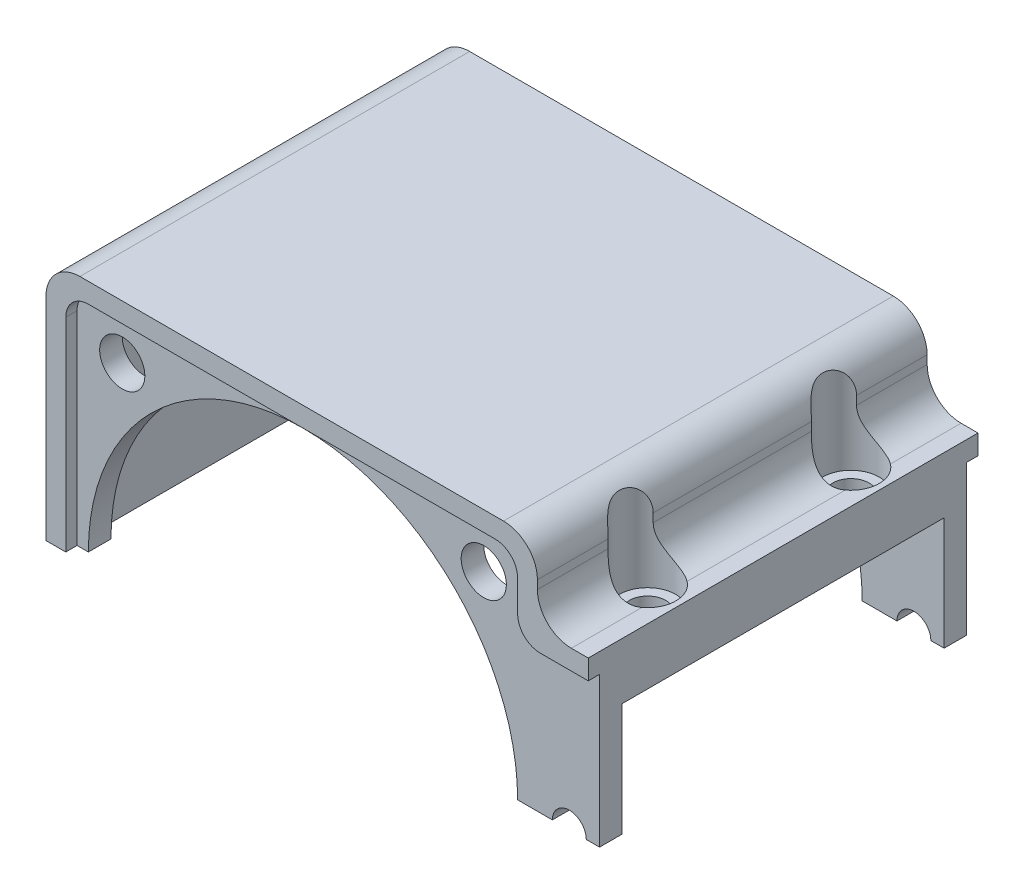
SolidWorks part; units mm, degrees
ref_plane "前视基准面" through (0, 0, 0) normal (0, 0, 1) x (1, 0, 0)
ref_plane "上视基准面" through (0, 0, 0) normal (0, 1, 0) x (1, 0, 0)
ref_plane "右视基准面" through (0, 0, 0) normal (1, 0, 0) x (0, 0, -1)
sketch "草图1" plane through (0, 0, 0) normal (0, 0, 1) x (1, 0, 0)
  line L5 (-20.25, 0) -> (-20.25, 17.25)
  line L6 (-17.25, 20.25) -> (17.25, 20.25)
  line L11 (23.25, 10) -> (26.25, 10)
  line L12 (20.25, 17.25) -> (20.25, 13)
  line L13 (-20.25, 0) -> (-21.75, 0)
  line L15 (0, 21.75) -> (-18.75, 21.75)
  line L16 (-21.75, 18.75) -> (-21.75, 0)
  line L17 (26.25, 10) -> (26.25, 15)
  line L21 (26.25, 15) -> (24.75, 15)
  line L22 (18.75, 21.75) -> (0, 21.75)
  line L23 (21.75, 18) -> (21.75, 18.75)
  arc A0 (24.75, 15) -> (21.75, 18) centre (24.75, 18) cw
  arc A1 (20.25, 13) -> (23.25, 10) centre (23.25, 13) ccw
  arc A2 (21.75, 18.75) -> (18.75, 21.75) centre (18.75, 18.75) ccw
  arc A3 (17.25, 20.25) -> (20.25, 17.25) centre (17.25, 17.25) cw
  arc A4 (-20.25, 17.25) -> (-17.25, 20.25) centre (-17.25, 17.25) cw
  arc A5 (-18.75, 21.75) -> (-21.75, 18.75) centre (-18.75, 18.75) ccw
  dimension "D1" = 3
extrude "凸台-拉伸1" add sketch "草图1" along normal blind 28.5
sketch "草图2" plane through (0, 0, 28.5) normal (0, 0, 1) x (1, 0, 0)
  line L0 (-21.75, 0) -> (26.25, 0)
  line L1 (26.25, 0) -> (26.25, 15)
  line L2 (26.25, 15) -> (24.75, 15)
  line L3 (21.75, 18) -> (21.75, 18.75)
  line L4 (18.75, 21.75) -> (-18.75, 21.75)
  line L5 (-21.75, 18.75) -> (-21.75, 0)
  arc A0 (24.75, 15) -> (21.75, 18) centre (24.75, 18) cw
  arc A1 (21.75, 18.75) -> (18.75, 21.75) centre (18.75, 18.75) ccw
  arc A2 (-18.75, 21.75) -> (-21.75, 18.75) centre (-18.75, 18.75) ccw
  dimension "D1" = 3
extrude "凸台-拉伸2" add sketch "草图2" along normal blind 3
sketch "草图3" plane through (0, 0, 0) normal (0, 0, -1) x (-1, 0, 0)
  line L0 (21.75, 0) -> (-26.25, 0)
  line L1 (-26.25, 0) -> (-26.25, 15)
  line L2 (-26.25, 15) -> (-24.75, 15)
  line L3 (-21.75, 18) -> (-21.75, 18.75)
  line L4 (-18.75, 21.75) -> (18.75, 21.75)
  line L5 (21.75, 18.75) -> (21.75, 0)
  arc A0 (-24.75, 15) -> (-21.75, 18) centre (-24.75, 18) ccw
  arc A1 (-21.75, 18.75) -> (-18.75, 21.75) centre (-18.75, 18.75) cw
  arc A2 (18.75, 21.75) -> (21.75, 18.75) centre (18.75, 18.75) cw
  dimension "D1" = 3
extrude "凸台-拉伸3" add sketch "草图3" along normal blind 3
sketch "草图4" plane through (0, 0, 31.5) normal (0, 0, 1) x (1, 0, 0)
  line L0 (26.25, 13.25) -> (26.25, 0)
  line L1 (-21.75, 0) -> (26.25, 0) construction
  line L2 (-20, 0) -> (-20, 18)
  line L3 (-18, 20) -> (18, 20)
  line L4 (26.25, 0) -> (-20, 0)
  line L5 (26.25, 0) -> (26.25, 15) construction
  line L6 (26.25, 13.25) -> (22, 13.25)
  line L7 (20, 15.25) -> (20, 18)
  arc A0 (18, 20) -> (20, 18) centre (18, 18) cw
  arc A1 (22, 13.25) -> (20, 15.25) centre (22, 15.25) cw
  arc A2 (-20, 18) -> (-18, 20) centre (-18, 18) cw
  dimension "D1" = 2
extrude "切除-拉伸1" cut sketch "草图4" against normal blind 1
sketch "草图5" plane through (0, 0, -3) normal (0, 0, -1) x (-1, 0, 0)
  line L0 (0, 0) -> (20, 0)
  line L1 (-26.25, 0) -> (21.75, 0) construction
  line L2 (20, 0) -> (20, 18)
  line L3 (18, 20) -> (-18, 20)
  line L4 (0, 0) -> (-26.25, 0)
  line L5 (-26.25, 15) -> (-26.25, 0) construction
  line L6 (-26.25, 13.25) -> (-22, 13.25)
  line L7 (-20, 15.25) -> (-20, 18)
  line L8 (-26.25, 0) -> (-26.25, 13.25)
  arc A0 (-22, 13.25) -> (-20, 15.25) centre (-22, 15.25) ccw
  arc A1 (-18, 20) -> (-20, 18) centre (-18, 18) ccw
  arc A2 (20, 18) -> (18, 20) centre (18, 18) ccw
  dimension "D1" = 2
extrude "切除-拉伸2" cut sketch "草图5" against normal blind 1
sketch "草图6" plane through (0, 0, 30.5) normal (0, 0, 1) x (1, 0, 0)
  line L0 (22.074, 0) -> (25.074, 0)
  line L36 (-11.5439, 13.6652) -> (-5.0528, 7.1742)
  line L39 (-1.5, 17.8255) -> (-1.5, 8.6458)
  line L40 (1.5, 17.8255) -> (1.5, 8.6458)
  line L43 (11.5439, 13.6652) -> (5.0528, 7.1742)
  line L44 (13.6652, 11.5439) -> (7.1742, 5.0528)
  line L47 (17.8255, 1.5) -> (8.6458, 1.5)
  line L52 (-4, 0) -> (4, 0)
  line L53 (-17.8255, 1.5) -> (-8.6458, 1.5)
  line L58 (-13.6652, 11.5439) -> (-7.1742, 5.0528)
  circle A0 centre (-16, 16) radius 2
  circle A1 centre (16, 16) radius 2
  arc A3 (22.074, 0) -> (25.074, 0) centre (23.574, 0) cw
  arc A7 (-4, 0) -> (4, 0) centre (0, 0) cw
  arc A9 (18.8159, 2.6389) -> (17.8255, 1.5) centre (17.8255, 2.5) cw
  arc A35 (-18.8159, 2.6389) -> (-15.1708, 11.4388) centre (0, 0) cw
  arc A36 (-7.6852, 2.2222) -> (-7.0056, 3.8629) centre (0, 0) cw
  arc A37 (-3.8629, 7.0056) -> (-2.2222, 7.6852) centre (0, 0) cw
  arc A38 (2.2222, 7.6852) -> (3.8629, 7.0056) centre (0, 0) cw
  arc A39 (7.0056, 3.8629) -> (7.6852, 2.2222) centre (0, 0) cw
  arc A40 (-11.4388, 15.1708) -> (-2.6389, 18.8159) centre (0, 0) cw
  arc A41 (2.6389, 18.8159) -> (11.4388, 15.1708) centre (0, 0) cw
  arc A42 (15.1708, 11.4388) -> (18.8159, 2.6389) centre (0, 0) cw
  arc A45 (13.6652, 11.5439) -> (15.1708, 11.4388) centre (14.3723, 10.8368) cw
  arc A46 (11.4388, 15.1708) -> (11.5439, 13.6652) centre (10.8368, 14.3723) cw
  arc A47 (1.5, 17.8255) -> (2.6389, 18.8159) centre (2.5, 17.8255) cw
  arc A48 (-1.5, 17.8255) -> (-2.6389, 18.8159) centre (-2.5, 17.8255) ccw
  arc A49 (-11.5439, 13.6652) -> (-11.4388, 15.1708) centre (-10.8368, 14.3723) cw
  arc A50 (7.6852, 2.2222) -> (8.6458, 1.5) centre (8.6458, 2.5) ccw
  arc A51 (7.0056, 3.8629) -> (7.1742, 5.0528) centre (7.8813, 4.3457) cw
  arc A52 (3.8629, 7.0056) -> (5.0528, 7.1742) centre (4.3457, 7.8813) ccw
  arc A53 (1.5, 8.6458) -> (2.2222, 7.6852) centre (2.5, 8.6458) ccw
  arc A54 (-1.5, 8.6458) -> (-2.2222, 7.6852) centre (-2.5, 8.6458) cw
  arc A55 (-3.8629, 7.0056) -> (-5.0528, 7.1742) centre (-4.3457, 7.8813) cw
  arc A56 (-7.0056, 3.8629) -> (-7.1742, 5.0528) centre (-7.8813, 4.3457) ccw
  arc A57 (-7.6852, 2.2222) -> (-8.6458, 1.5) centre (-8.6458, 2.5) cw
  arc A58 (-17.8255, 1.5) -> (-18.8159, 2.6389) centre (-17.8255, 2.5) cw
  arc A59 (-15.1708, 11.4388) -> (-13.6652, 11.5439) centre (-14.3723, 10.8368) cw
  point P72 (0, 0)
  dimension "D1" = 1
extrude "切除-拉伸3" cut sketch "草图6" against normal blind 33
sketch "草图7" plane through (0, 15, 0) normal (0, 1, 0) x (1, 0, 0)
  circle A0 centre (23.25, -5.25) radius 1.6
  circle A1 centre (23.25, -23.25) radius 1.6
extrude "切除-拉伸5" cut sketch "草图7" along normal blind 6 and the other way blind 6
sketch "草图8" plane through (0, 15, 0) normal (0, 1, 0) x (1, 0, 0)
  circle A0 centre (23.25, -5.25) radius 2.5
  circle A1 centre (23.25, -23.25) radius 2.5
extrude "切除-拉伸6" cut sketch "草图8" along normal blind 6 and the other way blind 2
sketch "草图9" plane through (0, 0, 0) normal (0, 0, 1) x (1, 0, 0)
  line L0 (-20, 0) -> (-4, 0) construction
  line L1 (4, 0) -> (22.074, 0) construction
  line L2 (-19, 0) -> (19, 0)
  arc A0 (-17.5537, 7.271) -> (-19, 0) centre (0, 0) ccw
  arc A1 (-15.1708, 11.4388) -> (-18.8159, 2.6389) centre (0, 0) ccw construction
  arc A2 (-17.5537, 7.271) -> (19, 0) centre (0, 0) cw
extrude "切除-拉伸7" cut sketch "草图9" against normal up to surface (32.5 mm away) from surface at 30.5 up to face at (9.3257, 9.5126, -2) starting at face at (4.9995, 12.0698, 30.5)
